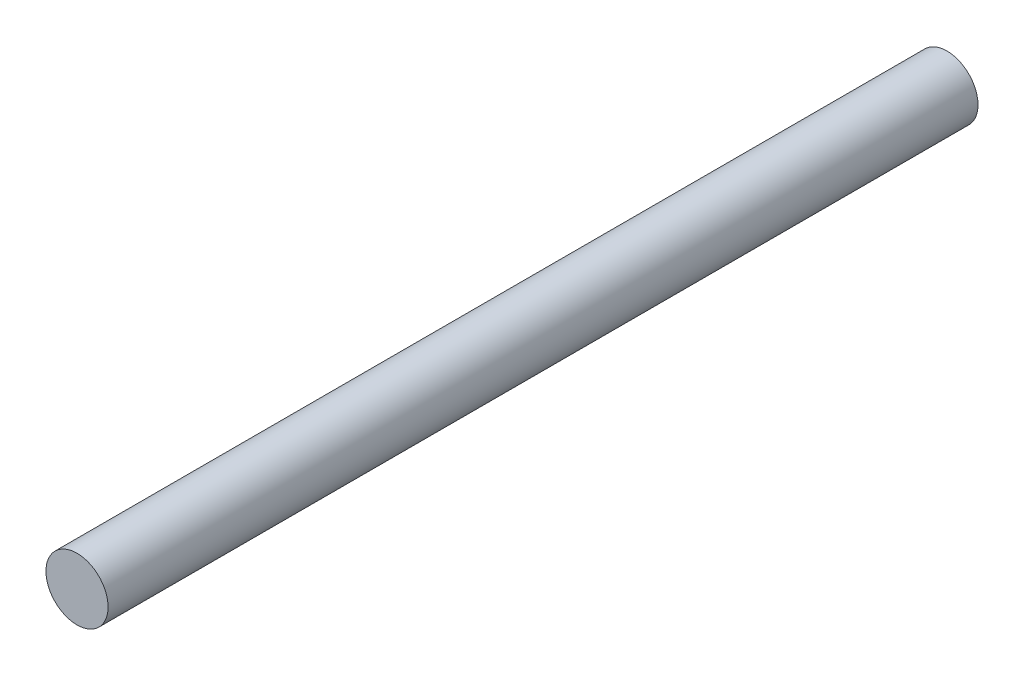
SolidWorks part; units mm, degrees
ref_plane "Front Plane" through (0, 0, 0) normal (0, 0, 1) x (1, 0, 0)
ref_plane "Top Plane" through (0, 0, 0) normal (0, 1, 0) x (1, 0, 0)
ref_plane "Right Plane" through (0, 0, 0) normal (1, 0, 0) x (0, 0, -1)
sketch "Sketch1" plane through (0, 0, 0) normal (0, 0, 1) x (1, 0, 0)
  circle A0 centre (0, 0) radius 6.35
  dimension "D1" = 12.7
extrude "Boss-Extrude1" add sketch "Sketch1" along normal blind 177.8
